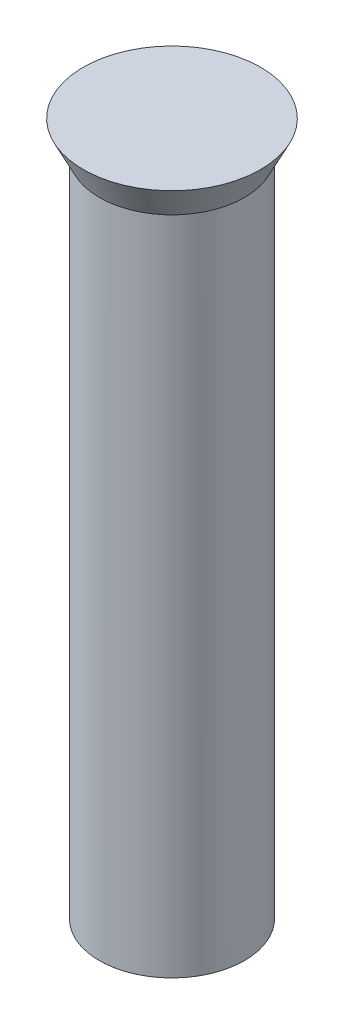
SolidWorks part; units mm, degrees
ref_plane "Front Plane" through (0, 0, 0) normal (0, 0, 1) x (1, 0, 0)
ref_plane "Top Plane"
ref_plane "Right Plane" through (0, 0, 0) normal (1, 0, 0) x (0, 0, -1)
sketch "Sketch1" plane through (0, 0, 0) normal (0, 1, 0) x (1, 0, 0)
  circle A1 centre (0, 0) radius 9
extrude "Boss-Extrude1" add sketch "Sketch1" along normal blind 80
sketch "Sketch2" plane through (0, 0, 0) normal (0, -1, 0) x (1, 0, 0)
  circle A0 centre (0, 0) radius 9
extrude "Boss-Extrude2" add sketch "Sketch2" along normal blind 2
sketch "Sketch4" plane through (0, 0, 0) normal (1, 0, 0) x (0, 0, -1)
  line L0 (9, 80) -> (11, 80) construction
  line L2 (9, 80) -> (0, 80)
  line L8 (9, 80) -> (11, 84.0079)
  line L14 (11, 84.0079) -> (0, 84.0079)
  line L15 (0, 80) -> (0, 84.0079)
  line L16 (0, 75.0152) -> (0, 88.9927) construction
  point P7 (0, 82.0039)
revolve "Revolve1" add sketch "Sketch4" angle 360 about L16
